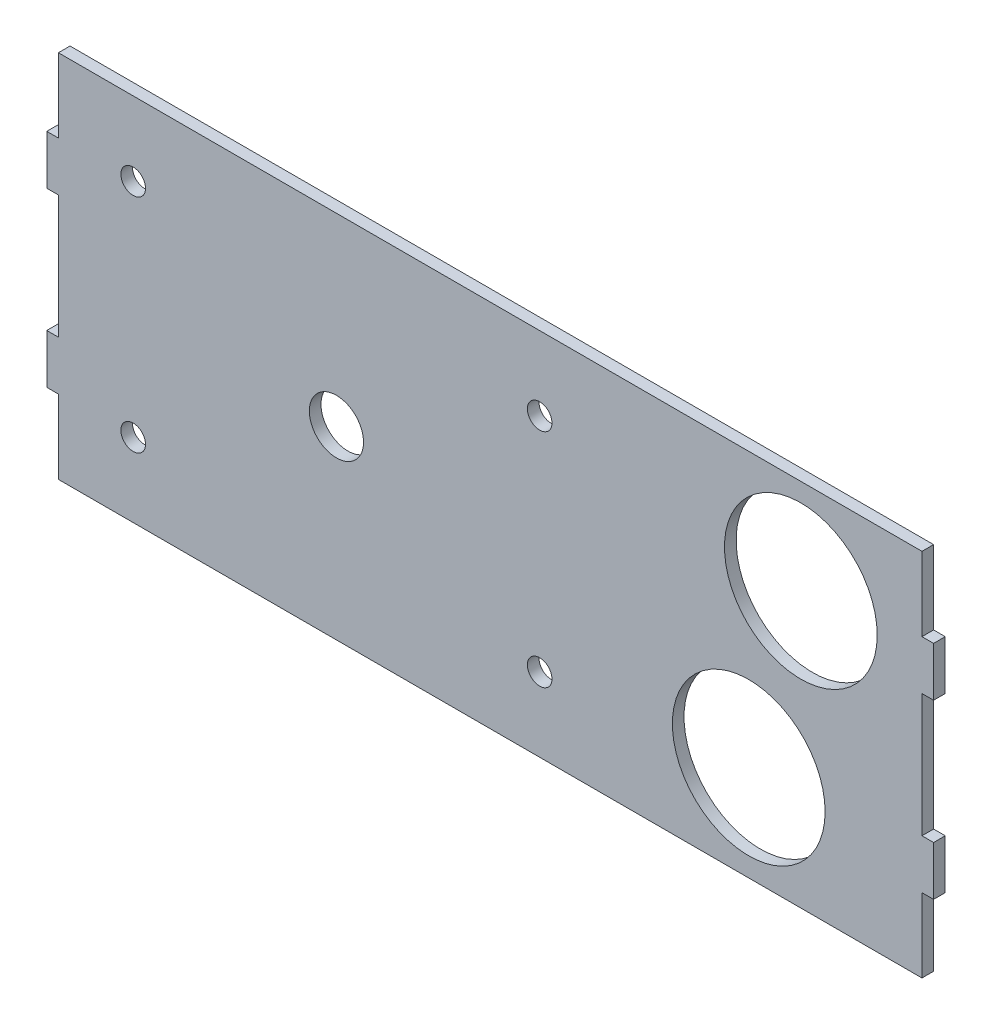
SolidWorks part; units mm, degrees
ref_plane "Front Plane" through (0, 0, 0) normal (0, 0, 1) x (1, 0, 0)
ref_plane "Top Plane" through (0, 0, 0) normal (0, 1, 0) x (1, 0, 0)
ref_plane "Right Plane" through (0, 0, 0) normal (1, 0, 0) x (0, 0, -1)
sketch "Sketch1" plane through (0, 0, 0) normal (0, 0, 1) x (1, 0, 0)
  line L0 (-119.3631, 35.9946) -> (-119.3631, 20.9946)
  line L1 (-119.3631, 35.9946) -> (55.9125, 35.9946)
  line L3 (-119.3631, -39.0054) -> (55.9125, -39.0054)
  line L5 (-119.3631, 20.9946) -> (-121.7253, 20.9946)
  line L6 (-121.7253, 20.9946) -> (-121.7253, 10.9946)
  line L7 (-121.7253, 10.9946) -> (-119.3631, 10.9946)
  line L8 (-119.3631, 10.9946) -> (-119.3631, -14.0054)
  line L9 (-119.3631, -14.0054) -> (-121.7253, -14.0054)
  line L10 (-121.7253, -14.0054) -> (-121.7253, -24.0054)
  line L11 (-121.7253, -24.0054) -> (-119.3631, -24.0054)
  line L12 (-119.3631, -24.0054) -> (-119.3631, -39.0054)
  line L13 (55.9125, 35.9946) -> (55.9125, 20.9946)
  line L14 (55.9125, 20.9946) -> (58.2747, 20.9946)
  line L15 (58.2747, 20.9946) -> (58.2747, 10.9946)
  line L16 (58.2747, 10.9946) -> (55.9125, 10.9946)
  line L17 (55.9125, 10.9946) -> (55.9125, -14.0054)
  line L18 (55.9125, -14.0054) -> (58.2747, -14.0054)
  line L19 (58.2747, -14.0054) -> (58.2747, -24.0054)
  line L20 (58.2747, -24.0054) -> (55.9125, -24.0054)
  line L21 (55.9125, -24.0054) -> (55.9125, -39.0054)
  dimension "D1" = 75
  dimension "D2" = 15
  dimension "D3" = 10
  dimension "D4" = 10
  dimension "D5" = 15
  dimension "D6" = 15
  dimension "D7" = 15
  dimension "D8" = 10
  dimension "D9" = 10
  dimension "D10" = 2.3622
  dimension "D11" = 2.3622
  dimension "D12" = 2.3622
  dimension "D13" = 2.3622
  dimension "D14" = 2.3622
  dimension "D15" = 2.3622
  dimension "D16" = 2.3622
  dimension "D17" = 2.3622
  dimension "D18" = 180
extrude "Boss-Extrude1" add sketch "Sketch1" along normal blind 2.3622
sketch "Sketch2" plane through (0, 0, 2.3622) normal (0, 0, 1) x (1, 0, 0)
  line L1 (-119.3631, 10.9946) -> (-119.3631, -14.0054) construction
  circle A0 centre (31.3281, 16.7215) radius 15.5
  circle A3 centre (20.7537, -19.6113) radius 15.5
  circle A4 centre (-62.932, -1.5054) radius 5.5
  circle A5 centre (-104.182, 20.9946) radius 2.5
  circle A6 centre (-21.682, 20.9946) radius 2.5
  circle A7 centre (-21.682, -24.0054) radius 2.5
  circle A8 centre (-104.182, -24.0054) radius 2.5
  point P2 (19.886, 15.9946)
  point P3 (33.5364, -16.3573)
  point P4 (25.9529, 15.9946)
  point P5 (33.8398, -18.1773)
  point P16 (16.1443, 15.0947)
  point P17 (12.8906, -18.5267)
  point P20 (-65.3074, 0)
  point P21 (-71.0564, -1.5367)
  point P22 (-109.0342, 29.144)
  point P23 (0, 0)
  point P26 (-119.3631, -1.5054)
  point P27 (-104.182, 28.4946)
  point P28 (31.3281, 16.7215)
  point P29 (20.7537, -19.6113)
  dimension "D1" = 31
  dimension "D5" = 11
  dimension "D10" = 5
  dimension "D6" = 41.25
  dimension "D7" = 22.5
  dimension "D8" = 45
  dimension "D9" = 82.5
extrude "Cut-Extrude1" cut sketch "Sketch2" against normal through all
